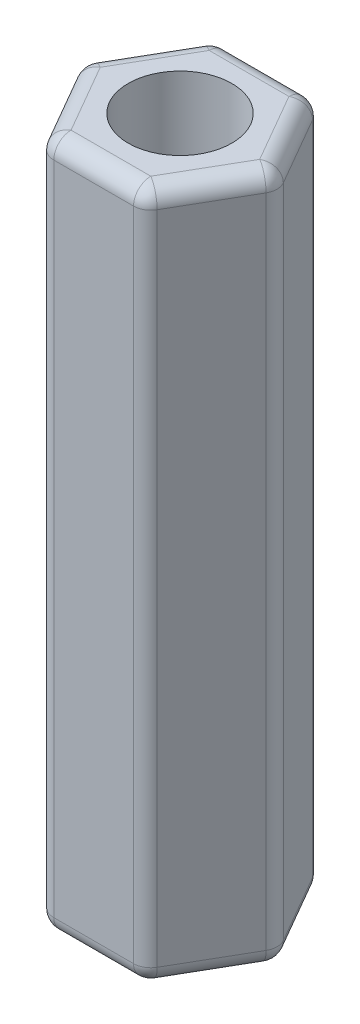
SolidWorks part; units mm, degrees
material "Brass"
ref_plane "Front Plane" through (0, 0, 0) normal (0, 0, 1) x (1, 0, 0)
ref_plane "Top Plane" through (0, 0, 0) normal (0, 1, 0) x (1, 0, 0)
ref_plane "Right Plane" through (0, 0, 0) normal (1, 0, 0) x (0, 0, -1)
sketch "Sketch1" plane through (0, 0, 0) normal (0, 1, 0) x (1, 0, 0)
  line L1 (-1.4434, 2.5) -> (-2.8868, 0)
  line L2 (-2.8868, 0) -> (-1.4434, -2.5)
  line L3 (-1.4434, -2.5) -> (1.4434, -2.5)
  line L4 (1.4434, -2.5) -> (2.8868, 0)
  line L5 (2.8868, 0) -> (1.4434, 2.5)
  line L6 (1.4434, 2.5) -> (-1.4434, 2.5)
  circle A0 centre (0, 0) radius 2.5 construction
  circle A1 centre (0, 0) radius 1.5
  dimension "D2" = 3
  dimension "D1" = 5
extrude "Boss-Extrude1" add sketch "Sketch1" along normal blind 20
fillet "Fillet1" radius 0.5 18 edges at (0, 20, -2.5) (0, 0, -2.5) (2.1651, 20, -1.25) (1.4434, 10, -2.5) (2.1651, 0, -1.25) (2.1651, 20, 1.25) (2.8868, 10, 0) (2.1651, 0, 1.25) (-2.1651, 20, 1.25) (-2.1651, 0, 1.25) (-1.4434, 10, -2.5) (-2.1651, 20, -1.25) (-2.8868, 10, 0) (-2.1651, 0, -1.25) (-1.4434, 10, 2.5) (0, 20, 2.5) (1.4434, 10, 2.5) (0, 0, 2.5)
